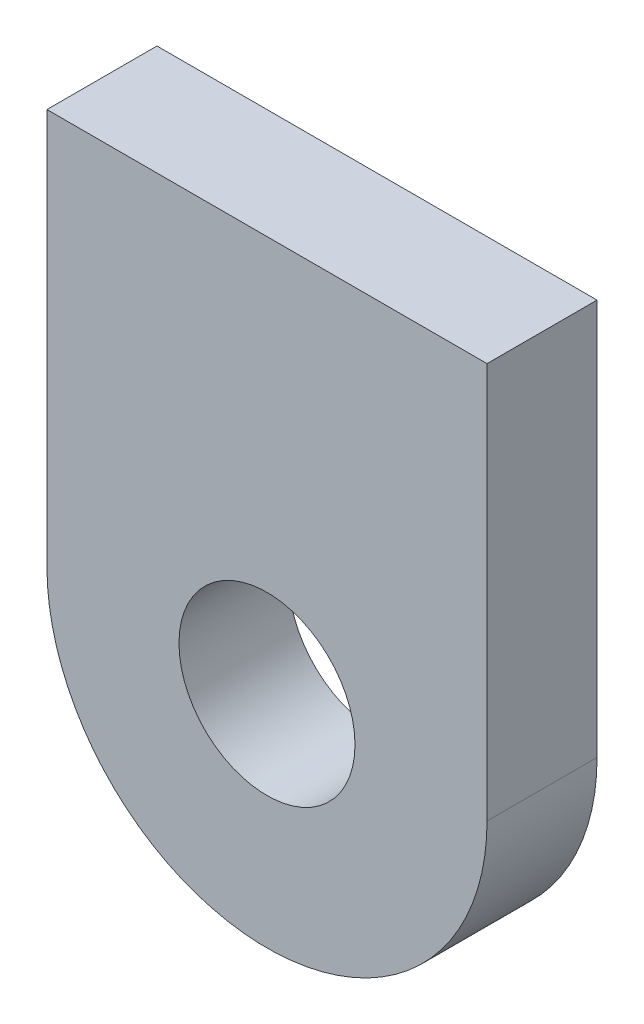
SolidWorks part; units mm, degrees
ref_plane "Ön Düzlem" through (0, 0, 0) normal (0, 0, 1) x (1, 0, 0)
ref_plane "Üst Düzlem" through (0, 0, 0) normal (0, 1, 0) x (1, 0, 0)
ref_plane "Sağ Düzlem" through (0, 0, 0) normal (1, 0, 0) x (0, 0, -1)
sketch "Çizim1" plane through (0, 0, 0) normal (0, 0, 1) x (1, 0, 0)
  line L1 (-10, 15) -> (-10, 0)
  line L2 (10, 0) -> (10, 15)
  line L3 (-10, 15) -> (-10, 18)
  line L4 (-10, 18) -> (10, 18)
  line L5 (10, 18) -> (10, 15)
  arc A0 (-10, 0) -> (10, 0) centre (0, 0) ccw
  circle A1 centre (0, 0) radius 4
  dimension "D1" = 3
extrude "Yükseklik-Ekstrüzyon1" add sketch "Çizim1" along normal blind 5
